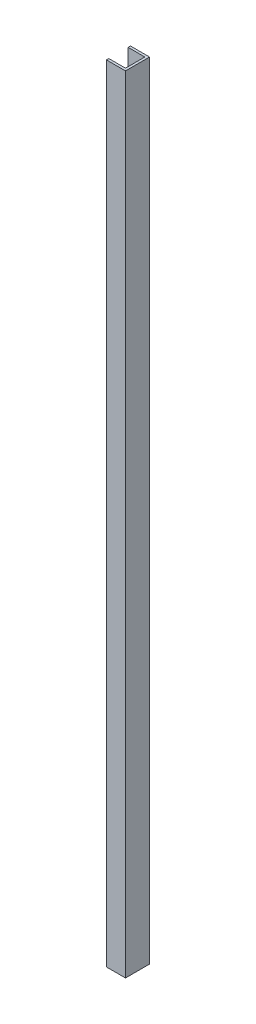
SolidWorks part; units mm, degrees
ref_plane "Front Plane" through (0, 0, 0) normal (0, 0, 1) x (1, 0, 0)
ref_plane "Top Plane" through (0, 0, 0) normal (0, 1, 0) x (1, 0, 0)
ref_plane "Right Plane" through (0, 0, 0) normal (1, 0, 0) x (0, 0, -1)
sketch "side channel sketch" plane through (0, 0, 0) normal (0, 1, 0) x (1, 0, 0)
  line L0 (154.32, -13.83) -> (167.02, -13.83)
  line L1 (167.02, -13.83) -> (167.02, -29.87)
  line L2 (167.02, -29.87) -> (154.32, -29.87)
  line L3 (154.32, -29.87) -> (154.32, -28.3)
  line L4 (154.32, -28.3) -> (165.45, -28.3)
  line L5 (165.45, -28.3) -> (165.45, -15.4)
  line L6 (165.45, -15.4) -> (154.32, -15.4)
  line L7 (154.32, -15.4) -> (154.32, -13.83)
extrude "side channel" add sketch "side channel sketch" along normal mid plane 523.94
equation "\"diffL\" = 608.8mm"
equation "\"diffW\" = 329.4mm"
equation "\"diffT\" = 2.9mm"
equation "\"chanSlotW\" = 12.9mm"
equation "\"chanSlotDepth\" = 11.13mm"
equation "\"chanFloor\" = 1.57mm"
equation "\"chanLeg\" = 12.7mm"
equation "\"lightL\" = 604.8mm"
equation "\"lightW\" = 330.2mm"
equation "\"lightH\" = 92mm"
equation "\"lightSideFlat\" = 30mm"
equation "\"lightSlopeLen\" = 38.9mm"
equation "\"lightWingDepth\" = 50.1mm"
equation "\"lightWingFlat\" = 90.2mm"
equation "\"lightChanW\" = 99.6mm"
equation "\"lightChanStand\" = 44.1mm"
equation "\"insFlangeD\" = 12.3mm"
equation "\"insFromEnd\" = 20.7mm"
equation "\"insUpSlope\" = 20.8mm"
equation "\"gaugeH\" = 10mm"
equation "\"gaugeStepLen\" = 14mm"
equation "\"gaugeStepW0\" = 13.1mm"
equation "\"gaugeStepDW\" = 0.2mm"
equation "\"gaugeSteps\" = 5mm"
equation "\"gaugeHandleLen\" = 30mm"
equation "\"gaugeHandleW\" = 24mm"
equation "\"gaugeSlot0\" = 3mm"
equation "\"gaugeSlotD\" = 0.1mm"
equation "\"gaugeSlotDepth\" = 8mm"
equation "\"gap\" = 25.4mm"
equation "\"edgeL\" = 1mm"
equation "\"edgeW\" = 0.75mm"
equation "\"proud\" = 2.5mm"
equation "\"seatClr\" = 0.15mm"
equation "\"tongueClrZ\" = 0.1mm"
equation "\"tongueClrX\" = 0.25mm"
equation "\"tongueLen\" = 30mm"
equation "\"armSide\" = 45mm"
equation "\"armEnd\" = 20mm"
equation "\"brkW\" = 26mm"
equation "\"brkT\" = 7mm"
equation "\"brkSeatClr\" = 0.3mm"
equation "\"brkScrewSpan\" = 16mm"
equation "\"pilotD\" = 2.7mm"
equation "\"pilotDepth\" = 10mm"
equation "\"screwClrD\" = 3.9mm"
equation "\"jogBelow\" = 4mm"
equation "\"padT\" = 7mm"
equation "\"padLen\" = 36mm"
equation "\"m6Clr\" = 9mm"
equation "\"m6Slot\" = 5mm"
equation "\"flangeRelD\" = 18mm"
equation "\"flangeRelDepth\" = 1.5mm"
equation "\"relLen\" = 5mm"
equation "\"relDepth\" = 3.3mm"
equation "\"knockN\" = 100mm"
equation "\"petgcfE\" = 3000mm"
equation "\"mockExtent\" = 110mm"
equation "\"relZnear\" = 9.4mm"
equation "\"relZfar\" = 23.4mm"
equation "\"headD\" = 8mm"
equation "\"headH\" = 2.5mm"
equation "\"headFromEnd\" = 6.8mm"
equation "\"headBack\" = 16.4mm"
equation "\"sideClr\" = 0.4mm"
equation "\"cornerRelR\" = 1.5mm"
equation "\"cornerRelBack\" = 0.6mm"
equation "\"endHeadH\" = 2.8mm"
equation "\"footClr\" = 1.2mm"
equation "\"footEndClr\" = 3.5mm"
equation "\"footLift\" = 6mm"
equation "\"footBlockClr\" = 0.5mm"
equation "\"footBack\" = 50mm"
equation "\"footFwd\" = 10mm"
equation "\"footBraceEnd\" = 3mm"
equation "\"footLoadN\" = 25mm"
equation "\"spacerLen\" = 60mm"
equation "\"spacerShort\" = 0.5mm"
equation "\"spacerCham\" = 0.8mm"
equation "\"spacerPerSide\" = 3mm"
equation "\"spacerPerEnd\" = 1mm"
equation "\"toolR\" = 9mm"
equation "\"visR\" = 4mm"
equation "\"edgeR\" = 1mm"
equation "\"bendOutR\" = 5mm"
equation "\"insideR\" = 2.5mm"
equation "\"footCornerR\" = 10mm"
equation "\"footFrontR\" = 8mm"
equation "\"braceKinkR\" = 12mm"
equation "\"bedCham\" = 1mm"
equation "\"bedChamSmall\" = 0.6mm"
equation "\"soleTopR\" = 2mm"
equation "\"cornerR\" = 6mm"
equation "\"rimInR\" = 1mm"
equation "\"insFlangeH\" = 1mm"
